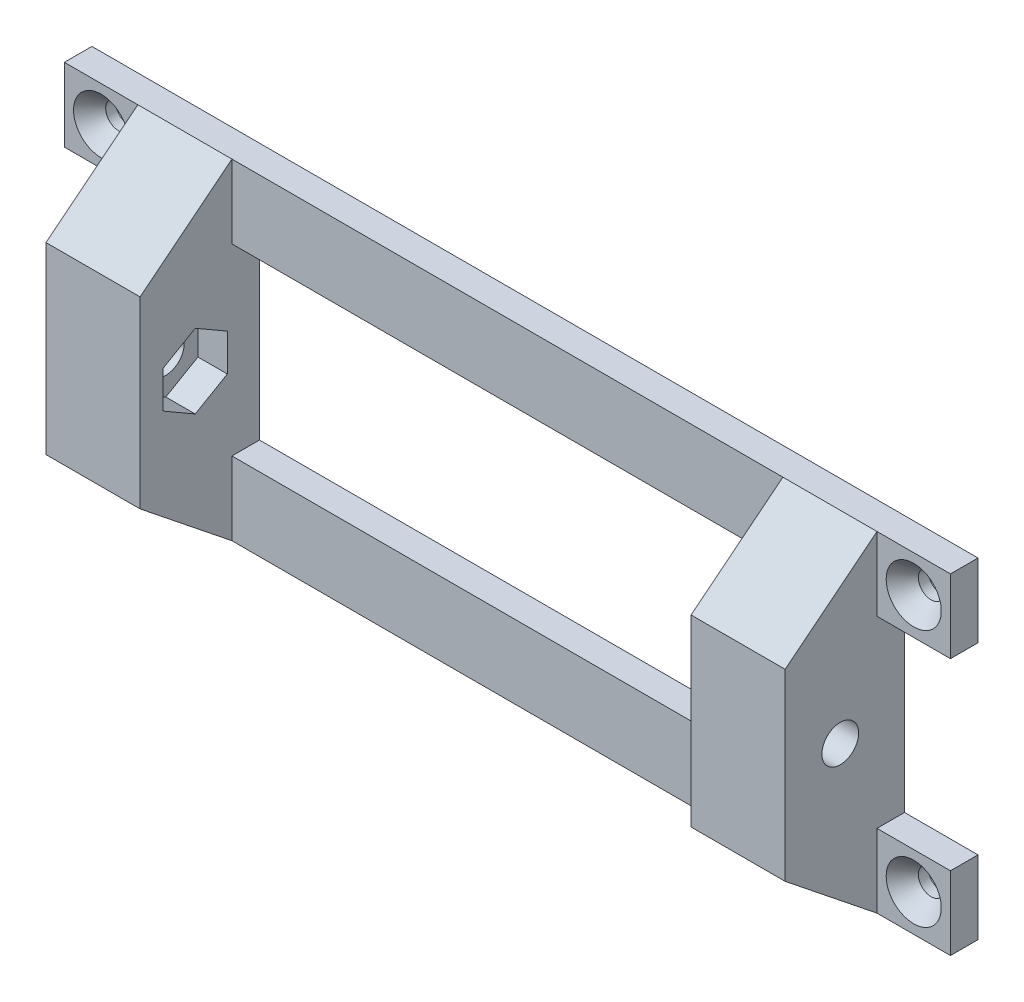
SolidWorks part; units mm, degrees
ref_plane "정면" through (0, 0, 0) normal (0, 0, 1) x (1, 0, 0)
ref_plane "윗면" through (0, 0, 0) normal (0, 1, 0) x (1, 0, 0)
ref_plane "우측면" through (0, 0, 0) normal (1, 0, 0) x (0, 0, -1)
sketch "스케치1" plane through (0, 0, 0) normal (0, 0, 1) x (1, 0, 0)
  line L0 (0, 0) -> (0, 18) construction
  line L1 (-48.25, 18) -> (48.25, 18)
  line L2 (-40.25, 10) -> (-40.25, -10)
  line L3 (-48.25, -18) -> (48.25, -18)
  line L4 (40.25, 10) -> (40.25, -10)
  line L6 (-30, -10) -> (30, -10)
  line L9 (-40.25, 10) -> (-48.25, 10)
  line L10 (-48.25, 18) -> (-48.25, 10)
  line L11 (0, 0) -> (-40.25, 0) construction
  line L12 (-40.25, -10) -> (-48.25, -10)
  line L13 (-48.25, -18) -> (-48.25, -10)
  line L16 (48.25, -18) -> (48.25, -10)
  line L17 (40.25, -10) -> (48.25, -10)
  line L18 (48.25, 18) -> (48.25, 10)
  line L19 (40.25, 10) -> (48.25, 10)
  line L20 (-30, -10) -> (-30, 10)
  line L21 (-30, 10) -> (30, 10)
  line L22 (30, -10) -> (30, 10)
  line L23 (-30, -10) -> (30, 10) construction
  line L24 (-30, 10) -> (30, -10) construction
  point P0 (0, 0)
  dimension "D1" = 96.5
  dimension "D2" = 36
  dimension "D3" = 8
  dimension "D4" = 8
  dimension "D5" = 60
extrude "보스-돌출1" add sketch "스케치1" along normal blind 3
sketch "스케치2" plane through (0, 0, 3) normal (0, 0, 1) x (1, 0, 0)
  line L1 (40.25, 10) -> (30, 10)
  line L2 (40.25, 10) -> (40.25, -10)
  line L3 (40.25, -10) -> (30, -10)
  line L4 (30, 10) -> (30, -10)
  line L5 (-40.25, 10) -> (-30, 10)
  line L6 (-40.25, 10) -> (-40.25, -10)
  line L7 (-40.25, -10) -> (-30, -10)
  line L8 (-30, 10) -> (-30, -10)
extrude "보스-돌출2" add sketch "스케치2" along normal blind 10 contours L2 L1 L4 L3 | L6 L5 L8 L7
sketch "스케치3" plane through (0, 0, 0) normal (1, 0, 0) x (0, 0, -1)
  line L0 (-7, 0) -> (0, 0) construction
  circle A0 centre (-7, 0) radius 2
  dimension "D1" = 4
  dimension "D2" = 7
extrude "컷-돌출1" cut sketch "스케치3" against normal through all both and the other way through all
sketch "스케치4" plane through (0, 0, 0) normal (0, 0, 1) x (1, 0, 0)
  line L0 (0, 0) -> (0, 18) construction
  line L1 (48.25, 18) -> (-48.25, 18) construction
  line L2 (0, 0) -> (40.25, 0) construction
  line L3 (40.25, 10) -> (40.25, -10) construction
  line L4 (40.25, 0) -> (0, 0) construction
  line L5 (40.25, 10) -> (48.25, 18) construction
  circle A0 centre (44.25, 14) radius 1.4
  circle A1 centre (-44.25, 14) radius 1.4
  circle A2 centre (44.25, -14) radius 1.4
  circle A3 centre (-44.25, -14) radius 1.4
  dimension "D1" = 2.8
extrude "컷-돌출2" cut sketch "스케치4" along normal through all
sketch "스케치5" plane through (40.25, 0, 0) normal (1, 0, 0) x (0, 0, -1)
  line L0 (-13, 10) -> (-3, 18)
  line L1 (-3, 18) -> (-3, 10)
  line L2 (-3, 10) -> (-13, 10)
  line L3 (-13, -10) -> (-3, -10)
  line L4 (-3, -10) -> (-3, -18)
  line L5 (-3, -18) -> (-13, -10)
extrude "보스-돌출3" add sketch "스케치5" against normal up to surface (10.25 mm away) up to face at (30, 0, 9)
sketch "스케치6" plane through (-40.25, 0, 0) normal (-1, 0, 0) x (0, 0, 1)
  line L0 (3, 18) -> (3, 10)
  line L1 (3, 10) -> (13, 10)
  line L2 (13, 10) -> (3, 18)
  line L3 (3, -10) -> (3, -18)
  line L4 (3, -18) -> (13, -10)
  line L5 (13, -10) -> (3, -10)
extrude "보스-돌출4" add sketch "스케치6" against normal up to surface (10.25 mm away) up to face at (-30, 0, 5)
sketch "스케치7" plane through (30, 0, 0) normal (-1, 0, 0) x (0, 0, 1)
  line L1 (7, 4.0415) -> (3.5, 2.0207)
  line L2 (3.5, 2.0207) -> (3.5, -2.0207)
  line L3 (3.5, -2.0207) -> (7, -4.0415)
  line L4 (7, -4.0415) -> (10.5, -2.0207)
  line L5 (10.5, -2.0207) -> (10.5, 2.0207)
  line L6 (10.5, 2.0207) -> (7, 4.0415)
  circle A0 centre (7, 0) radius 3.5 construction
  dimension "D1" = 7
extrude "컷-돌출3" cut sketch "스케치7" against normal blind 3.2
mirror "대칭 복사2" about plane through (0, 0, 0) normal (1, 0, 0) of "컷-돌출3"
chamfer "모따기1" distance 1.6 distance2 1.9 4 edges at (42.85, 14, 3) (-45.65, 14, 3) (-45.65, -14, 3) (42.85, -14, 3)
